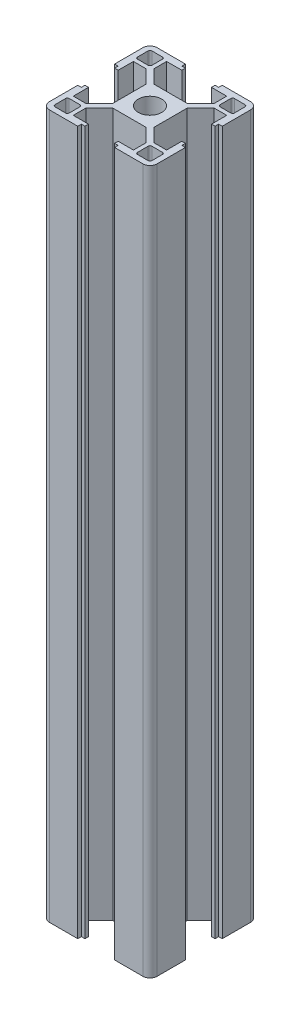
SolidWorks part; units mm, degrees
material "6061 Alloy"
ref_plane "Front Plane" through (0, 0, 0) normal (0, 0, 1) x (1, 0, 0)
ref_plane "Top Plane" through (0, 0, 0) normal (0, 1, 0) x (1, 0, 0)
ref_plane "Right Plane" through (0, 0, 0) normal (1, 0, 0) x (0, 0, -1)
sketch "Sketch1" plane through (0, 0, 0) normal (0, 1, 0) x (1, 0, 0)
  line L0 (-8.375, 13) -> (-4.125, 13)
  line L1 (-13, 15) -> (-4.125, 15)
  line L2 (-15, 13) -> (-15, 4.125)
  line L3 (-13, -15) -> (-4.125, -15)
  line L4 (15, 13) -> (15, 4.125)
  line L5 (-15, 15) -> (15, -15) construction
  line L6 (-15, -15) -> (15, 15) construction
  line L7 (-11.5, 11.5) -> (11.5, 11.5) construction
  line L8 (-11.5, 11.5) -> (-11.5, -11.5) construction
  line L9 (-11.5, -11.5) -> (11.5, -11.5) construction
  line L10 (11.5, 11.5) -> (11.5, -11.5) construction
  line L11 (-11.5, 11.5) -> (11.5, -11.5) construction
  line L12 (-11.5, -11.5) -> (11.5, 11.5) construction
  line L13 (-13.5, 13.5) -> (-9.5, 13.5)
  line L14 (-13.5, 13.5) -> (-13.5, 9.5)
  line L15 (-13.5, 9.5) -> (-9.5, 9.5)
  line L16 (-9.5, 13.5) -> (-9.5, 9.5)
  line L17 (-13.5, 13.5) -> (-9.5, 9.5) construction
  line L18 (-13.5, 9.5) -> (-9.5, 13.5) construction
  line L19 (13.5, 13.5) -> (9.5, 13.5)
  line L20 (13.5, 13.5) -> (13.5, 9.5)
  line L21 (13.5, 9.5) -> (9.5, 9.5)
  line L22 (9.5, 13.5) -> (9.5, 9.5)
  line L23 (13.5, 13.5) -> (9.5, 9.5) construction
  line L24 (13.5, 9.5) -> (9.5, 13.5) construction
  line L25 (13.5, -13.5) -> (9.5, -13.5)
  line L26 (13.5, -13.5) -> (13.5, -9.5)
  line L27 (13.5, -9.5) -> (9.5, -9.5)
  line L28 (9.5, -13.5) -> (9.5, -9.5)
  line L29 (13.5, -13.5) -> (9.5, -9.5) construction
  line L30 (13.5, -9.5) -> (9.5, -13.5) construction
  line L31 (-13.5, -13.5) -> (-9.5, -13.5)
  line L32 (-13.5, -13.5) -> (-13.5, -9.5)
  line L33 (-13.5, -9.5) -> (-9.5, -9.5)
  line L34 (-9.5, -13.5) -> (-9.5, -9.5)
  line L35 (-13.5, -13.5) -> (-9.5, -9.5) construction
  line L36 (-13.5, -9.5) -> (-9.5, -13.5) construction
  line L37 (0, 15) -> (0, 13) construction
  line L38 (-4.125, 15) -> (-4.125, 13)
  line L39 (4.125, 15) -> (4.125, 13)
  line L40 (4.125, 15) -> (13, 15)
  line L41 (-15, 15) -> (15, 15) construction
  line L42 (4.125, 13) -> (8.375, 13)
  line L43 (-15, 13) -> (15, 13) construction
  line L44 (8.375, 9.5064) -> (4.6186, 5.75)
  line L45 (-4.6186, -5.75) -> (4.6186, -5.75)
  line L46 (-8.375, 13) -> (-8.375, 9.5)
  line L47 (8.375, 13) -> (8.375, 9.5)
  line L48 (-8.375, 15) -> (-8.375, 13) construction
  line L49 (8.375, 15) -> (8.375, 13) construction
  line L50 (-5.75, -4.6186) -> (-5.75, 4.6186)
  line L51 (-4.6186, 5.75) -> (4.6186, 5.75)
  line L52 (5.75, -4.6186) -> (5.75, 4.6186)
  line L53 (-5.75, -5.75) -> (5.75, 5.75) construction
  line L54 (-5.75, 5.75) -> (5.75, -5.75) construction
  line L55 (-8.375, 9.5064) -> (-4.6186, 5.75)
  line L56 (-10.6314, 9.5) -> (-5.75, 4.6186)
  line L57 (-14.4343, 15.5657) -> (15.5657, -14.4343) construction
  line L58 (15, 4.125) -> (13, 4.125)
  line L59 (13, 8.375) -> (13, 4.125)
  line L60 (13, 8.375) -> (9.5, 8.375)
  line L61 (9.5064, 8.375) -> (5.75, 4.6186)
  line L62 (9.5064, -8.375) -> (5.75, -4.6186)
  line L63 (13, -8.375) -> (9.5, -8.375)
  line L64 (13, -4.125) -> (13, -8.375)
  line L65 (15, -4.125) -> (13, -4.125)
  line L66 (4.125, -15) -> (4.125, -13)
  line L67 (8.375, -13) -> (4.125, -13)
  line L68 (8.375, -13) -> (8.375, -9.5)
  line L69 (8.375, -9.5064) -> (4.6186, -5.75)
  line L70 (-8.375, -9.5064) -> (-4.6186, -5.75)
  line L71 (-8.375, -13) -> (-8.375, -9.5)
  line L72 (-4.125, -13) -> (-8.375, -13)
  line L73 (-4.125, -15) -> (-4.125, -13)
  line L74 (-15, -4.125) -> (-13, -4.125)
  line L75 (-13, -8.375) -> (-13, -4.125)
  line L76 (-13, -8.375) -> (-9.5, -8.375)
  line L77 (-9.5064, -8.375) -> (-5.75, -4.6186)
  line L78 (-9.5064, 8.375) -> (-5.75, 4.6186)
  line L79 (-13, 8.375) -> (-9.5, 8.375)
  line L80 (-13, 4.125) -> (-13, 8.375)
  line L81 (-15, 4.125) -> (-13, 4.125)
  line L82 (-15, -4.125) -> (-15, -13)
  line L83 (4.125, -15) -> (13, -15)
  line L84 (15, -4.125) -> (15, -13)
  circle A0 centre (0, 0) radius 3.25
  circle A1 centre (0, 0) radius 3.25
  circle A2 centre (0, 0) radius 3.25
  circle A3 centre (0, 0) radius 3.25
  arc A4 (-15, -13) -> (-13, -15) centre (-13, -13) ccw
  arc A5 (13, -15) -> (15, -13) centre (13, -13) ccw
  arc A6 (13, 15) -> (15, 13) centre (13, 13) cw
  arc A7 (-13, 15) -> (-15, 13) centre (-13, 13) ccw
  point P0 (0, 0)
  point P6 (0, 0)
  point P31 (0, 0)
  point P48 (-15.5657, 14.4343)
  point P49 (14.4343, -15.5657)
  point P60 (0, 5.75)
  point P102 (0, 0)
  dimension "D17" = 6.5
  dimension "D10" = 2
  dimension "D1" = 30
  dimension "D2" = 30
  dimension "D3" = 23
  dimension "D4" = 23
  dimension "D5" = 4
  dimension "D6" = 4
  dimension "D7" = 4
  dimension "D8" = 4
  dimension "D12" = 3.5
  dimension "D16" = 11.5
  dimension "D11" = 11.5
  dimension "D9" = 2
  dimension "D18" = 0.8
extrude "Boss-Extrude1" add sketch "Sketch1" along normal blind 196
sketch "Sketch2" plane through (0, 196, 0) normal (0, 1, 0) x (1, 0, 0)
  line L0 (15, 4.125) -> (14, 4.125)
  line L1 (-4.125, 15) -> (-5.125, 15)
  line L2 (-4.125, 15) -> (-4.125, 14)
  line L3 (-4.125, 14) -> (-5.125, 14)
  line L4 (-5.125, 15) -> (-5.125, 14)
  line L5 (4.125, 15) -> (5.125, 15)
  line L6 (4.125, 15) -> (4.125, 14)
  line L7 (4.125, 14) -> (5.125, 14)
  line L8 (5.125, 15) -> (5.125, 14)
  line L9 (15, 4.125) -> (15, 5.125)
  line L10 (15, 5.125) -> (14, 5.125)
  line L11 (14, 4.125) -> (14, 5.125)
  line L12 (15, -4.125) -> (14, -4.125)
  line L13 (15, -4.125) -> (15, -5.125)
  line L14 (15, -5.125) -> (14, -5.125)
  line L15 (14, -4.125) -> (14, -5.125)
  line L16 (4.125, -15) -> (4.125, -14)
  line L17 (4.125, -15) -> (5.125, -15)
  line L18 (5.125, -15) -> (5.125, -14)
  line L19 (4.125, -14) -> (5.125, -14)
  line L20 (-4.125, -15) -> (-4.125, -14)
  line L21 (-4.125, -15) -> (-5.125, -15)
  line L22 (-5.125, -15) -> (-5.125, -14)
  line L23 (-4.125, -14) -> (-5.125, -14)
  line L24 (-15, -4.125) -> (-14, -4.125)
  line L25 (-15, -4.125) -> (-15, -5.125)
  line L26 (-15, -5.125) -> (-14, -5.125)
  line L27 (-14, -4.125) -> (-14, -5.125)
  line L28 (-15, 4.125) -> (-14, 4.125)
  line L29 (-15, 4.125) -> (-15, 5.125)
  line L30 (-15, 5.125) -> (-14, 5.125)
  line L31 (-14, 4.125) -> (-14, 5.125)
  point P36 (0, 0)
  dimension "D1" = 1
  dimension "D2" = 1
  dimension "D3" = 1
  dimension "D4" = 1
  dimension "D5" = 4
extrude "Cut-Extrude1" cut sketch "Sketch2" against normal through all
fillet "Fillet1" radius 0.5 16 edges at (9.5, 98, 13.5) (-13.5, 98, 13.5) (-13.5, 98, -9.5) (9.5, 98, -9.5) (-13.5, 98, 9.5) (9.5, 98, 9.5) (9.5, 98, -13.5) (-13.5, 98, -13.5) (-9.5, 98, -13.5) (13.5, 98, -13.5) (13.5, 98, 9.5) (-9.5, 98, 9.5) (13.5, 98, 13.5) (-9.5, 98, 13.5) (-9.5, 98, -9.5) (13.5, 98, -9.5)
